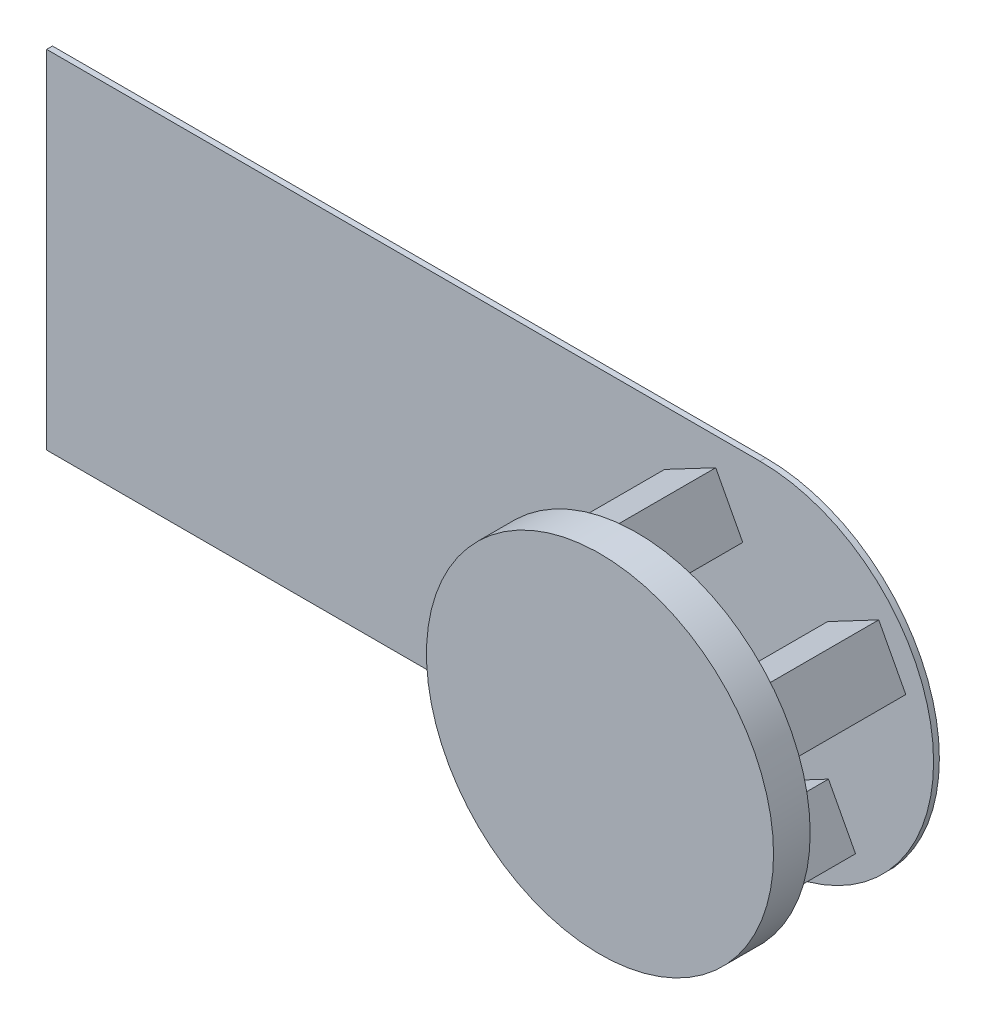
SolidWorks part; units mm, degrees
material "Balsa"
ref_plane "Alzado" through (0, 0, 0) normal (0, 0, 1) x (1, 0, 0)
ref_plane "Planta" through (0, 0, 0) normal (0, 1, 0) x (1, 0, 0)
ref_plane "Vista lateral" through (0, 0, 0) normal (1, 0, 0) x (0, 0, -1)
sketch "Sketch1" plane through (0, 0, 0) normal (0, 0, 1) x (1, 0, 0)
  line L1 (-131.9425, 0) -> (238.0575, 0)
  line L2 (-131.9425, 0) -> (-131.9425, 180)
  line L3 (-131.9425, 180) -> (238.0575, 180)
  arc A0 (238.0575, 0) -> (238.0575, 180) centre (238.0575, 90) ccw
  point P5 (328.0575, 90)
  dimension "D2" = 180
  dimension "D1" = 180
  dimension "D3" = 460
extrude "Boss-Extrude1" add sketch "Sketch1" along normal blind 3
sketch "Sketch2" plane through (0, 0, 3) normal (0, 0, 1) x (1, 0, 0)
  line L0 (238.0575, 169) -> (238.0575, 11) construction
  line L1 (176.5005, 40.485) -> (162.4779, 67.006)
  line L10 (162.4779, 67.006) -> (188.999, 81.0287)
  line L11 (188.999, 81.0287) -> (203.0216, 54.5076)
  line L12 (203.0216, 54.5076) -> (176.5005, 40.485)
  line L13 (215.0636, 165.5796) -> (229.0862, 139.0586)
  line L14 (202.5651, 125.0359) -> (188.5425, 151.557)
  line L15 (229.0862, 139.0586) -> (202.5651, 125.0359)
  line L16 (188.5425, 151.557) -> (215.0636, 165.5796)
  line L17 (313.6371, 112.994) -> (287.1161, 98.9713)
  line L18 (273.0935, 125.4924) -> (299.6145, 139.515)
  line L19 (287.1161, 98.9713) -> (273.0935, 125.4924)
  line L20 (299.6145, 139.515) -> (313.6371, 112.994)
  line L21 (261.0515, 14.4204) -> (247.0289, 40.9414)
  line L22 (273.5499, 54.9641) -> (287.5725, 28.443)
  line L23 (247.0289, 40.9414) -> (273.5499, 54.9641)
  line L24 (287.5725, 28.443) -> (261.0515, 14.4204)
  line L25 (187.7491, 76.9743) -> (198.9672, 55.7574)
  line L26 (198.9672, 55.7574) -> (177.7504, 44.5394)
  line L27 (177.7504, 44.5394) -> (166.5323, 65.7562)
  line L28 (166.5323, 65.7562) -> (187.7491, 76.9743)
  line L29 (272.3001, 50.9097) -> (283.5182, 29.6929)
  line L30 (283.5182, 29.6929) -> (262.3013, 18.4748)
  line L31 (262.3013, 18.4748) -> (251.0832, 39.6916)
  line L32 (251.0832, 39.6916) -> (272.3001, 50.9097)
  line L33 (277.1478, 124.2426) -> (298.3647, 135.4606)
  line L34 (298.3647, 135.4606) -> (309.5828, 114.2438)
  line L35 (309.5828, 114.2438) -> (288.3659, 103.0257)
  line L36 (288.3659, 103.0257) -> (277.1478, 124.2426)
  line L37 (213.8137, 161.5252) -> (225.0318, 140.3084)
  line L38 (225.0318, 140.3084) -> (203.815, 129.0903)
  line L39 (203.815, 129.0903) -> (192.5969, 150.3071)
  line L40 (192.5969, 150.3071) -> (213.8137, 161.5252)
  arc A0 (238.0575, 0) -> (238.0575, 180) centre (238.0575, 90) ccw construction
  arc A1 (238.0575, 0) -> (238.0575, 180) centre (238.0575, 90) ccw
  arc A2 (238.0575, 11) -> (238.0575, 169) centre (238.0575, 90) ccw
  arc A3 (238.0575, 11) -> (238.0575, 169) centre (238.0575, 90) cw
  arc A4 (159.0575, 90) -> (317.0575, 90) centre (238.0575, 90) ccw
  arc A5 (159.0575, 90) -> (317.0575, 90) centre (238.0575, 90) cw
  arc A6 (238.0575, 169) -> (238.0575, 11) centre (238.0575, 90) ccw
  arc A7 (238.0575, 169) -> (238.0575, 11) centre (238.0575, 90) cw
  arc A8 (317.0575, 90) -> (159.0575, 90) centre (238.0575, 90) ccw
  arc A9 (317.0575, 90) -> (159.0575, 90) centre (238.0575, 90) cw
  point P31 (238.0575, 90)
  dimension "D2" = 30
  dimension "D3" = 4
  dimension "D4" = 3
  dimension "D5" = 3
  dimension "D1" = 11
extrude "Boss-Extrude2" add sketch "Sketch2" along normal blind 64 contours L12 L11 L10 L1 L27 L28 L25 L26 | L24 L22 L23 L21 L31 L32 L29 L30 | L20 L18 L19 L17 L35 L36 L33 L34 | L16 L14 L15 L13 L39 L40 L37 L38
sketch "Sketch3" plane through (0, 0, 67) normal (0, 0, 1) x (1, 0, 0)
  circle A2 centre (238.0575, 90) radius 90
extrude "Boss-Extrude4" add sketch "Sketch3" along normal blind 19
